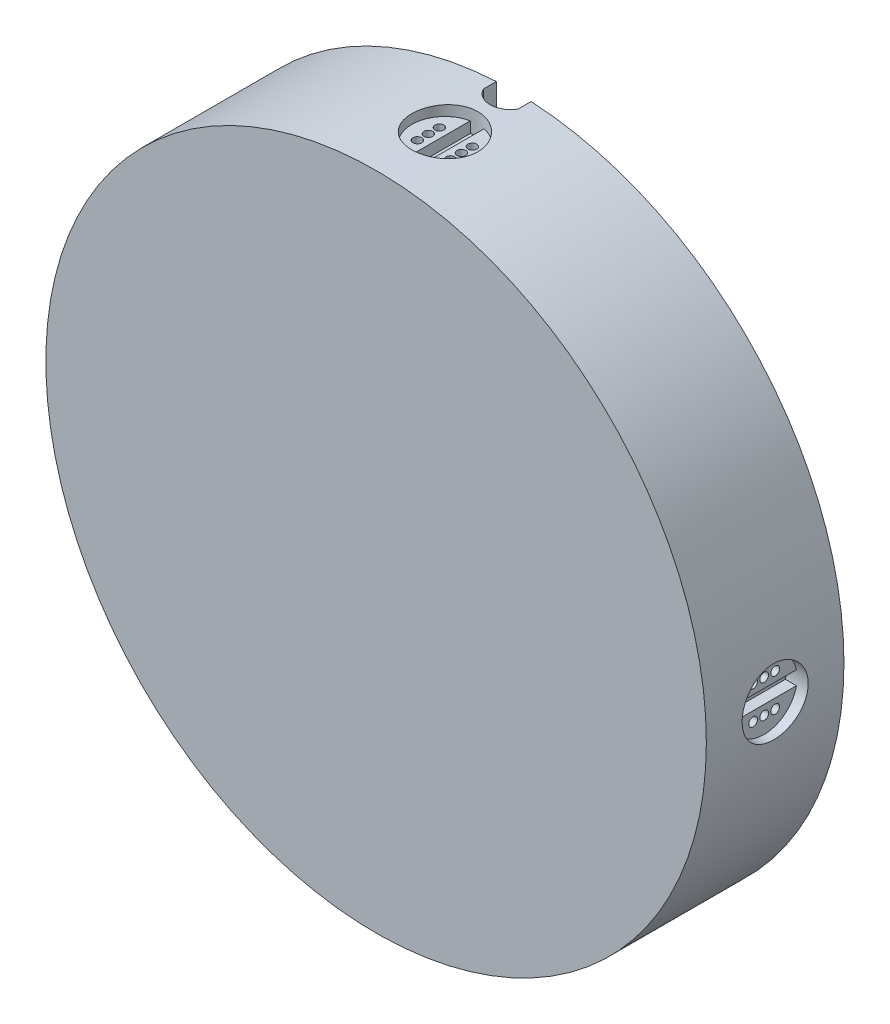
SolidWorks part; units mm, degrees
ref_plane "Front Plane" through (0, 0, 0) normal (1, 0, 0) x (0, 1, 0)
ref_plane "Top Plane" through (0, 0, 0) normal (0, 0, 1) x (0, 1, 0)
ref_plane "Right Plane" through (0, 0, 0) normal (0, 1, 0) x (-1, 0, 0)
sketch "Sketch3" plane through (0, 0, 0) normal (0, 0, 1) x (0, 1, 0)
  circle A0 centre (0, 0) radius 76.2
extrude "Boss-Extrude1" add sketch "Sketch3" against normal blind 31.75 contours A0
ref_plane "Plane1" through (0, 76.2, 0) normal (0, 1, 0) x (-1, 0, 0)
sketch "Sketch5" plane through (0, 76.2, 0) normal (0, 1, 0) x (-1, 0, 0)
  line L0 (0, 0) -> (0, -31.75) construction
  line L1 (-76.2, -31.75) -> (76.2, -31.75) construction
  circle A0 centre (0, -15.875) radius 7.62
extrude "Cut-Extrude1" cut sketch "Sketch5" against normal blind 2.54
sketch "Sketch6" plane through (0, 0, -31.75) normal (0, 0, -1) x (1, 0, 0)
  circle A0 centre (0, 0) radius 68.58
extrude "Cut-Extrude2" cut sketch "Sketch6" against normal blind 21.59
pattern_circular "CirPattern1" count 4 over 360 about axis through (0, 0, 0) along (0, 0, 1) of "Cut-Extrude1"
sketch "Sketch10" plane through (0, 0, 0) normal (1, 0, 0) x (0, 1, 0)
  line L0 (0, 0) -> (0, -31.75) construction
  line L1 (-76.2, -31.75) -> (76.2, -31.75) construction
sketch "Sketch12" plane through (73.66, 0, 0) normal (1, 0, 0) x (0, 1, 0)
  line L0 (0, -8.255) -> (0, -23.495) construction
  line L1 (0, 0) -> (0, -31.75) construction
  line L2 (0, -15.875) -> (3.81, -15.875) construction
  line L3 (3.81, -15.875) -> (3.81, -13.335) construction
  line L4 (3.81, -15.875) -> (3.81, -18.415) construction
  circle A0 centre (0, -15.875) radius 7.62 construction
  circle A1 centre (0, -15.875) radius 7.62 construction
  circle A2 centre (3.81, -18.415) radius 1.016
  circle A3 centre (3.81, -15.875) radius 1.016
  circle A4 centre (3.81, -13.335) radius 1.016
  circle A5 centre (-3.81, -18.415) radius 1.016
  circle A6 centre (-3.81, -15.875) radius 1.016
  circle A7 centre (-3.81, -13.335) radius 1.016
extrude "Cut-Extrude4" cut sketch "Sketch12" against normal up to surface (5.25 mm away)
pattern_circular "CirPattern6" count 4 over 360 about axis through (0, 0, 0) along (0, 0, 1) of "Cut-Extrude4"
sketch "Sketch14" plane through (73.66, 0, 0) normal (1, 0, 0) x (0, 1, 0)
  line L0 (0, 0) -> (0, -31.75) construction
  line L7 (-1.5875, -23.3278) -> (-1.5875, -8.4222)
  line L9 (1.5875, -23.3278) -> (1.5875, -8.4222)
  line L10 (-1.5875, -23.3278) -> (1.5875, -8.4222) construction
  line L11 (-1.5875, -8.4222) -> (1.5875, -23.3278) construction
  arc A0 (-1.5875, -8.4222) -> (1.5875, -8.4222) centre (0, -15.875) cw
  circle A1 centre (0, -15.875) radius 7.62 construction
  arc A2 (-1.5875, -23.3278) -> (1.5875, -23.3278) centre (0, -15.875) ccw
  point P0 (0, -15.875)
  point P1 (0, -15.875)
extrude "Cut-Extrude6" cut sketch "Sketch14" against normal blind 2.54
pattern_circular "CirPattern7" count 4 over 360 about axis through (0, 0, 0) along (0, 0, 1) of "Cut-Extrude6"
sketch "Sketch15" plane through (0, 0, -10.16) normal (0, 0, -1) x (1, 0, 0)
  line L0 (-5.7, 0) -> (5.7, 0) construction
  line L1 (-5.7, -23.5) -> (5.7, -23.5) construction
  line L2 (-5.7, -23.5) -> (-5.7, 23.5) construction
  line L3 (-5.7, 23.5) -> (5.7, 23.5) construction
  line L4 (5.7, -23.5) -> (5.7, 23.5) construction
  line L5 (-5.7, -23.5) -> (5.7, 23.5) construction
  line L6 (-5.7, 23.5) -> (5.7, -23.5) construction
  line L7 (-17.4625, 0) -> (17.4625, 0) construction
  circle A0 centre (-5.7, -23.5) radius 2.5
  circle A1 centre (-5.7, -23.5) radius 1.1
  circle A2 centre (4.3, -23.5) radius 2.5
  circle A3 centre (4.3, -23.5) radius 1.1
  circle A4 centre (4.3, 23.5) radius 2.5
  circle A5 centre (4.3, 23.5) radius 1.1
  circle A6 centre (-5.7, 23.5) radius 1.1
  circle A7 centre (-5.7, 23.5) radius 2.5
  point P0 (0, 0)
  dimension "D1" = 2
extrude "Boss-Extrude2" add sketch "Sketch15" along normal blind 10
sketch "Sketch16" plane through (0, 76.2, 0) normal (0, 1, 0) x (-1, 0, 0)
  line L0 (0, -31.75) -> (4, -31.75)
  line L1 (-76.2, -31.75) -> (76.2, -31.75) construction
  line L2 (0, -31.75) -> (-4, -31.75)
  line L3 (-4, -31.75) -> (-4, -28.75)
  line L4 (4, -31.75) -> (4, -28.75)
  arc A0 (-4, -28.75) -> (4, -28.75) centre (0, -30.786) cw
  point P8 (-41.2458, -29.1266)
extrude "Cut-Extrude7" cut sketch "Sketch16" against normal blind 10
ref_plane "Plane2" through (0, 0, -31.75) normal (0, 0, -1) x (-1, 0, 0)
sketch "Sketch19" plane through (0, 0, -31.75) normal (0, 0, -1) x (-1, 0, 0)
  line L0 (0, 0) -> (51.1875, 51.1875) construction
  circle A0 centre (51.1875, 51.1875) radius 2
  circle A1 centre (51.1875, -51.1875) radius 2
  circle A2 centre (-51.1875, -51.1875) radius 2
  circle A3 centre (-51.1875, 51.1875) radius 2
  point P13 (0, 0)
  dimension "D1" = 4
extrude "Cut-Extrude8" cut sketch "Sketch19" against normal blind 5
